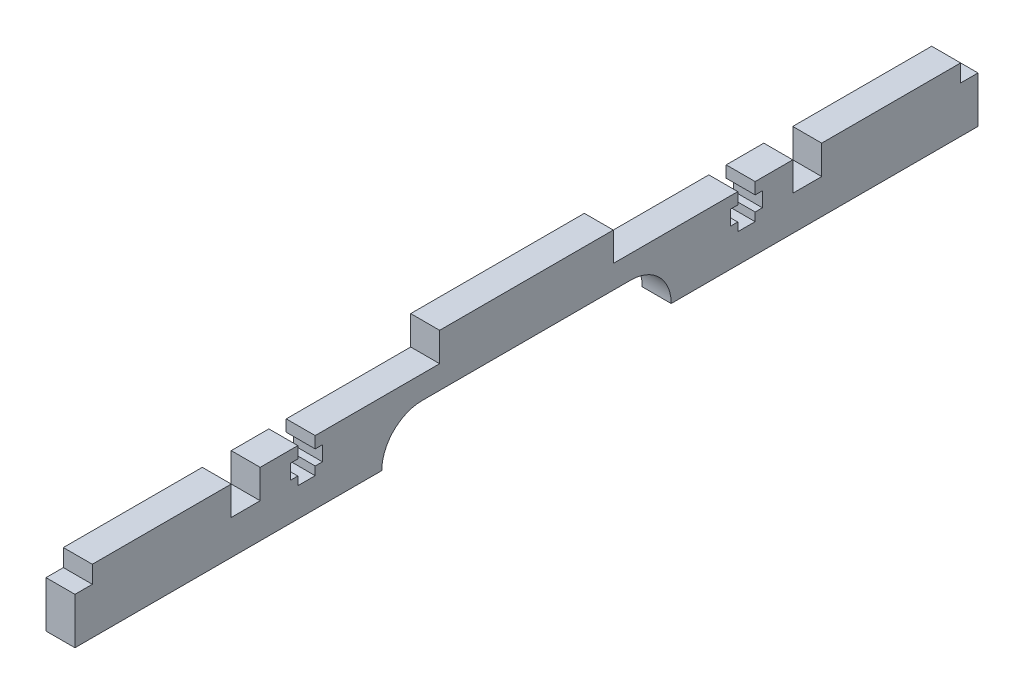
SolidWorks part; units mm, degrees
ref_plane "Front Plane" through (0, 0, 0) normal (0, 0, 1) x (1, 0, 0)
ref_plane "Top Plane" through (0, 0, 0) normal (0, 1, 0) x (1, 0, 0)
ref_plane "Right Plane" through (0, 0, 0) normal (1, 0, 0) x (0, 0, -1)
sketch "Sketch1" plane through (0, 0, 0) normal (0, 0, 1) x (1, 0, 0)
  line L0 (87.394, 57.0854) -> (91.394, 57.0854) construction
  line L1 (88.394, 57.0854) -> (83.394, 57.0854)
  line L2 (88.394, 57.0854) -> (88.394, 46.0854)
  line L3 (88.394, 46.0854) -> (83.394, 46.0854)
  line L4 (83.394, 57.0854) -> (83.394, 46.0854)
  line L5 (85.894, 46.0854) -> (85.894, 59.5854) construction
  dimension "D1" = 5
  dimension "D2" = 11
extrude "Boss-Extrude1" add sketch "Sketch1" along normal blind 150
sketch "Sketch2" plane through (88.394, 0, 0) normal (1, 0, 0) x (0, 0, -1)
  line L0 (-75, 46.0854) -> (-75, 57.0854) construction
  line L1 (-150, 46.0854) -> (0, 46.0854) construction
  line L2 (-150, 57.0854) -> (0, 57.0854) construction
  line L3 (-93, 53.0854) -> (-57, 53.0854)
  line L4 (-50, 46.0854) -> (-100, 46.0854)
  arc A0 (-57, 53.0854) -> (-50, 46.0854) centre (-57, 46.0854) cw
  arc A1 (-93, 53.0854) -> (-100, 46.0854) centre (-93, 46.0854) ccw
  point P14 (-75, 53.0854)
  dimension "D1" = 4
  dimension "D2" = 25
extrude "Cut-Extrude1" cut sketch "Sketch2" against normal through all
sketch "Sketch3" plane through (0, 57.0854, 0) normal (0, 1, 0) x (1, 0, 0)
  line L0 (88.394, -75) -> (83.394, -75) construction
  line L1 (88.394, -150) -> (88.394, 0) construction
  line L2 (83.394, -150) -> (83.394, 0) construction
  line L4 (88.394, -60) -> (83.394, -60)
  line L5 (88.394, -60) -> (88.394, -90)
  line L6 (88.394, -90) -> (83.394, -90)
  line L7 (83.394, -60) -> (83.394, -90)
  line L8 (88.394, -60) -> (83.394, -90) construction
  line L9 (88.394, -90) -> (83.394, -60) construction
  point P6 (85.894, -75)
  dimension "D1" = 30
extrude "Boss-Extrude2" add sketch "Sketch3" along normal blind 5
sketch "Sketch5" plane through (88.394, 0, 0) normal (1, 0, 0) x (0, 0, -1)
  line L0 (-37, 46.0854) -> (-37, 57.0854) construction
  line L1 (-75, 53.0854) -> (-75, 26.5602) construction
  line L2 (-35.5, 55.0854) -> (-34.25, 55.0854)
  line L3 (-35.5, 55.0854) -> (-35.5, 57.0854)
  line L4 (-50, 46.0854) -> (0, 46.0854) construction
  line L5 (-60, 57.0854) -> (0, 57.0854) construction
  line L6 (0, 46.0854) -> (0, 57.0854) construction
  line L7 (-38.5, 55.0854) -> (-38.5, 57.0854)
  line L8 (-38.5, 51.0854) -> (-35.5, 51.0854)
  line L9 (-38.5, 51.0854) -> (-38.5, 52.5354)
  line L10 (-38.5, 57.0854) -> (-35.5, 57.0854)
  line L11 (-35.5, 51.0854) -> (-35.5, 52.5354)
  line L12 (-38.5, 51.0854) -> (-35.5, 57.0854) construction
  line L13 (-38.5, 57.0854) -> (-35.5, 51.0854) construction
  line L14 (-39.75, 55.0854) -> (-38.5, 55.0854)
  line L15 (-39.75, 55.0854) -> (-39.75, 52.5354)
  line L16 (-39.75, 52.5354) -> (-38.5, 52.5354)
  line L17 (-34.25, 55.0854) -> (-34.25, 52.5354)
  line L18 (-39.75, 55.0854) -> (-34.25, 52.5354) construction
  line L19 (-39.75, 52.5354) -> (-34.25, 55.0854) construction
  line L20 (-35.5, 52.5354) -> (-34.25, 52.5354)
  line L21 (-57, 53.0854) -> (-93, 53.0854) construction
  line L22 (-110.25, 52.5354) -> (-115.75, 55.0854) construction
  line L23 (-110.25, 55.0854) -> (-115.75, 52.5354) construction
  line L24 (-111.5, 57.0854) -> (-114.5, 51.0854) construction
  line L25 (-111.5, 51.0854) -> (-114.5, 57.0854) construction
  line L26 (-114.5, 52.5354) -> (-115.75, 52.5354)
  line L27 (-115.75, 55.0854) -> (-115.75, 52.5354)
  line L28 (-110.25, 52.5354) -> (-111.5, 52.5354)
  line L29 (-110.25, 55.0854) -> (-110.25, 52.5354)
  line L30 (-110.25, 55.0854) -> (-111.5, 55.0854)
  line L31 (-114.5, 51.0854) -> (-114.5, 52.5354)
  line L32 (-111.5, 57.0854) -> (-114.5, 57.0854)
  line L33 (-111.5, 51.0854) -> (-111.5, 52.5354)
  line L34 (-111.5, 51.0854) -> (-114.5, 51.0854)
  line L35 (-111.5, 55.0854) -> (-111.5, 57.0854)
  line L36 (-114.5, 55.0854) -> (-114.5, 57.0854)
  line L37 (-114.5, 55.0854) -> (-115.75, 55.0854)
  point P8 (-37, 54.0854)
  point P13 (-37, 53.8104)
  point P39 (-113, 53.8104)
  point P40 (-113, 54.0854)
  dimension "D1" = 37
  dimension "D2" = 6
  dimension "D3" = 2
  dimension "D4" = 3
  dimension "D5" = 2.55
  dimension "D6" = 5.5
extrude "Cut-Extrude2" cut sketch "Sketch5" against normal through all
sketch "Sketch6" plane through (0, 0, 0) normal (0, 0, -1) x (-1, 0, 0)
  line L0 (-83.394, 57.0854) -> (-83.394, 46.0854) construction
  line L1 (-88.394, 46.0854) -> (-83.394, 46.0854)
  line L2 (-88.394, 46.0854) -> (-88.394, 54.0854)
  line L3 (-88.394, 54.0854) -> (-83.394, 54.0854)
  line L4 (-83.394, 46.0854) -> (-83.394, 54.0854)
  dimension "D1" = 8
extrude "Boss-Extrude3" add sketch "Sketch6" along normal blind 3
sketch "Sketch7" plane through (0, 0, 150) normal (0, 0, 1) x (1, 0, 0)
  line L4 (83.394, 46.0854) -> (88.394, 46.0854)
  line L5 (83.394, 54.0854) -> (83.394, 46.0854)
  line L6 (88.394, 54.0854) -> (83.394, 54.0854)
  line L7 (88.394, 46.0854) -> (88.394, 54.0854)
  line L8 (83.394, 46.0854) -> (88.394, 46.0854)
  line L9 (83.394, 54.0854) -> (83.394, 46.0854)
  line L10 (88.394, 54.0854) -> (83.394, 54.0854)
  line L11 (88.394, 46.0854) -> (88.394, 54.0854)
  dimension "D1" = 0
extrude "Boss-Extrude4" add sketch "Sketch7" along normal blind 3
sketch "Sketch8" plane through (88.394, 0, 0) normal (1, 0, 0) x (0, 0, -1)
  line L0 (-150, 57.0854) -> (-114.5, 57.0854) construction
  line L1 (-121, 57.0854) -> (-126, 57.0854)
  line L2 (-121, 57.0854) -> (-121, 52.0854)
  line L3 (-121, 52.0854) -> (-126, 52.0854)
  line L4 (-126, 57.0854) -> (-126, 52.0854)
  line L5 (-128, 66.5857) -> (-128, 34.6013) construction
  line L6 (-75, 62.0854) -> (-75, 19.7261) construction
  line L7 (-90, 62.0854) -> (-60, 62.0854) construction
  line L8 (-29, 57.0854) -> (-29, 52.0854)
  line L9 (-29, 57.0854) -> (-24, 57.0854)
  line L10 (-24, 57.0854) -> (-24, 52.0854)
  line L11 (-29, 52.0854) -> (-24, 52.0854)
  dimension "D1" = 5
  dimension "D2" = 2
  dimension "D3" = 5
extrude "Cut-Extrude3" cut sketch "Sketch8" against normal through all
